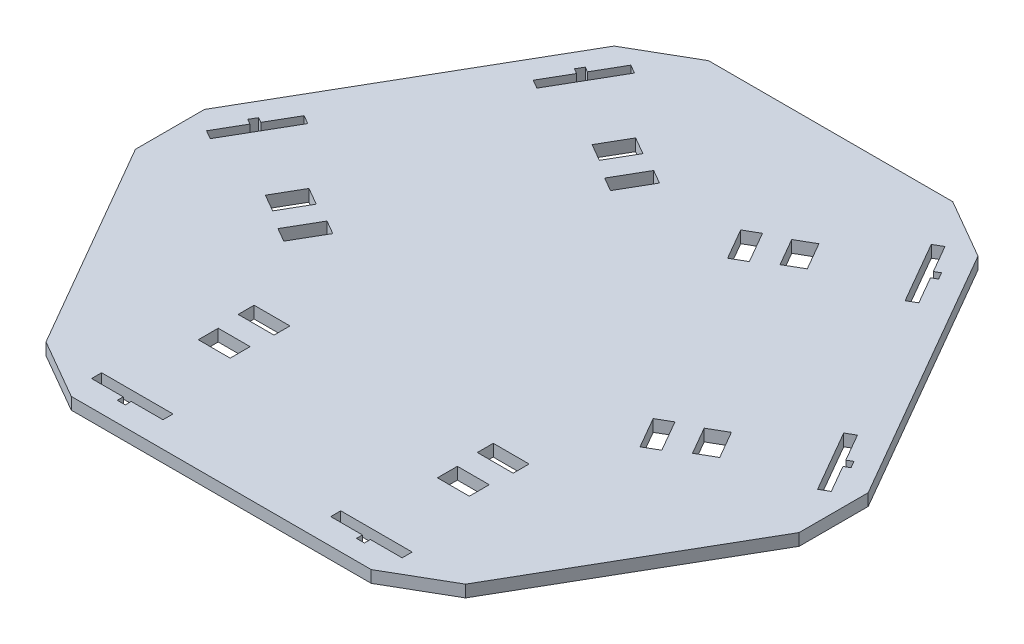
SolidWorks part; units mm, degrees
ref_plane "Front Plane" through (0, 0, 0) normal (0, 0, 1) x (1, 0, 0)
ref_plane "Top Plane" through (0, 0, 0) normal (0, 1, 0) x (1, 0, 0)
ref_plane "Right Plane" through (0, 0, 0) normal (1, 0, 0) x (0, 0, -1)
sketch "Sketch1" plane through (0, 0, 0) normal (0, 1, 0) x (1, 0, 0)
  line L0 (-40.64, 78.4561) -> (40.64, 78.4561)
  line L1 (40.64, 78.4561) -> (88.265, -4.0328)
  line L2 (88.265, -4.0328) -> (47.625, -74.4233)
  line L3 (47.625, -74.4233) -> (-47.625, -74.4233)
  line L4 (-47.625, -74.4233) -> (-88.265, -4.0328)
  line L5 (-88.265, -4.0328) -> (-40.64, 78.4561)
  line L6 (-64.4525, 37.2117) -> (64.4525, 37.2117) construction
  line L7 (64.4525, 37.2117) -> (0, -74.4233) construction
  line L8 (0, -74.4233) -> (-64.4525, 37.2117) construction
  line L9 (-67.945, -39.2281) -> (67.945, -39.2281) construction
  line L10 (-67.945, -39.2281) -> (0, 78.4561) construction
  line L11 (0, 78.4561) -> (67.945, -39.2281) construction
  circle A0 centre (0, 0) radius 78.4561 construction
  circle A1 centre (0, 0) radius 74.4233 construction
  point P9 (-67.945, -39.2281)
  point P10 (67.945, -39.2281)
  point P11 (67.945, -39.2281)
  point P14 (0, 78.4561)
  dimension "D1" = 60
  dimension "D2" = 60
  dimension "D3" = 81.28
  dimension "D4" = 95.25
extrude "Boss-Extrude1" add sketch "Sketch1" along normal blind 3
sketch "Sketch2" plane through (0, 3, 0) normal (0, 1, 0) x (1, 0, 0)
  line L4 (29, -68) -> (29, -69.5)
  line L5 (21.04, -65.48) -> (38.96, -65.48)
  line L6 (21.04, -65.48) -> (21.04, -68)
  line L7 (21.04, -68) -> (29, -68)
  line L8 (38.96, -65.48) -> (38.96, -68)
  line L9 (29, -69.5) -> (31, -69.5)
  line L10 (31, -69.5) -> (31, -68)
  line L11 (30, -69.5) -> (30, -65.48) construction
  line L12 (31, -68) -> (38.96, -68)
  point P4 (30, -65.48)
  dimension "D1" = 17.92
  dimension "D2" = 2.52
  dimension "D3" = 30
  dimension "D4" = 68
  dimension "D5" = 2
  dimension "D6" = 1.5
extrude "Cut-Extrude1" cut sketch "Sketch2" against normal through all
sketch "Sketch4" plane through (0, 3, 0) normal (0, 1, 0) x (1, 0, 0)
  line L0 (30, -65.48) -> (30, -46.18) construction
  line L1 (26, -41.18) -> (34, -41.18)
  line L2 (26, -41.18) -> (26, -46.18)
  line L3 (26, -46.18) -> (34, -46.18)
  line L4 (34, -41.18) -> (34, -46.18)
  line L5 (38.96, -65.48) -> (21.04, -65.48) construction
  line L6 (30, -41.18) -> (30, -35.68) construction
  line L7 (25.5, -31.68) -> (34.5, -31.68)
  line L8 (25.5, -31.68) -> (25.5, -35.68)
  line L9 (25.5, -35.68) -> (34.5, -35.68)
  line L10 (34.5, -31.68) -> (34.5, -35.68)
  point P8 (26, -43.68)
  point P16 (25.5, -33.68)
  dimension "D1" = 5
  dimension "D2" = 8
  dimension "D3" = 21.8
  dimension "D4" = 9
  dimension "D5" = 4
  dimension "D6" = 10
extrude "Cut-Extrude2" cut sketch "Sketch4" against normal through all
mirror "Mirror1" about plane through (0, 0, 0) normal (1, 0, 0) of "Cut-Extrude2", "Cut-Extrude1"
sketch "Sketch3" plane through (0, 0, 0) normal (1, 0, 0) x (0, 0, -1)
  line L0 (0, 57.1526) -> (0, 0) construction
pattern_circular "CirPattern1" count 3 over 360 about axis through (0, 0, 0) along (0, 1, 0) of "Mirror1", "Cut-Extrude1", "Cut-Extrude2"
chamfer "Chamfer1" distance 10 6 edges at (-88.265, 1.5, 4.0328) (-40.64, 1.5, -78.4561) (40.64, 1.5, -78.4561) (88.265, 1.5, 4.0328) (47.625, 1.5, 74.4233) (-47.625, 1.5, 74.4233)
